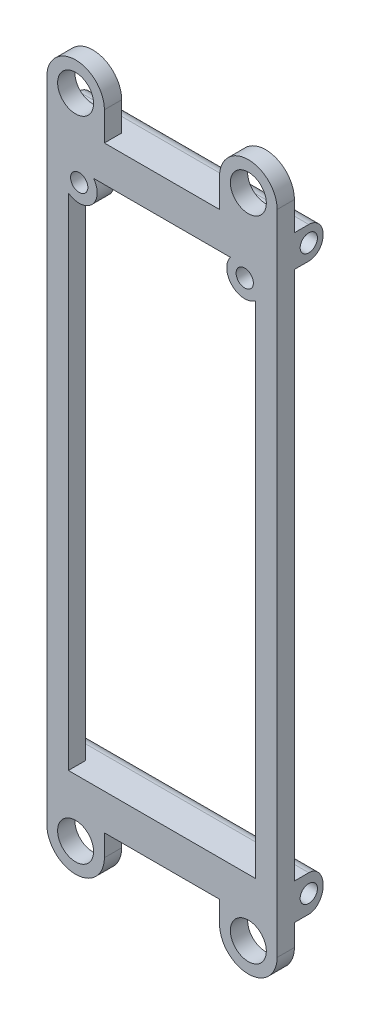
SolidWorks part; units mm, degrees
ref_plane "Front Plane" through (0, 0, 0) normal (0, 0, 1) x (1, 0, 0)
ref_plane "Top Plane" through (0, 0, 0) normal (0, 1, 0) x (1, 0, 0)
ref_plane "Right Plane" through (0, 0, 0) normal (1, 0, 0) x (0, 0, -1)
sketch "Sketch1" plane through (0, 0, 0) normal (0, 0, 1) x (1, 0, 0)
  line L0 (16, -82) -> (16, 1) construction
  line L1 (8, 1) -> (24, 1)
  line L2 (0, 0) -> (0, -80)
  line L3 (8, -82) -> (24, -82)
  line L4 (32, 0) -> (32, -80)
  line L5 (4, 5) -> (4, 0) construction
  line L6 (0, 0) -> (0, 18.809) construction
  line L7 (4, 5) -> (0, 5)
  line L8 (0, 5) -> (0, 0)
  line L9 (8, 5) -> (8, 1)
  line L10 (0, 5) -> (0, 0)
  line L11 (28, 5) -> (28, 2.5) construction
  line L12 (32, 5) -> (32, 0)
  line L13 (24, 5) -> (24, 1)
  line L14 (32, 5) -> (32, 0)
  line L15 (28, 5) -> (32, 5)
  line L16 (29, -4) -> (3, -4)
  line L17 (3, -4) -> (3, -77)
  line L18 (3, -77) -> (29, -77)
  line L19 (29, -4) -> (29, -77)
  line L20 (0, -40) -> (32, -40) construction
  line L21 (28, -85) -> (28, -82.5) construction
  line L22 (4, -85) -> (4, -80) construction
  line L23 (28, -85) -> (32, -85)
  line L24 (32, -85) -> (32, -80)
  line L25 (8, -85) -> (8, -82)
  line L26 (32, -85) -> (32, -80)
  line L27 (0, -85) -> (0, -80)
  line L28 (24, -85) -> (24, -82)
  line L29 (0, -85) -> (0, -80)
  line L30 (4, -85) -> (0, -85)
  circle A0 centre (4, 5) radius 2.5
  arc A1 (8, 5) -> (0, 5) centre (4, 5) ccw
  arc A2 (24, 5) -> (32, 5) centre (28, 5) cw
  circle A3 centre (28, 5) radius 2.5
  circle A4 centre (28, -85) radius 2.5
  arc A5 (24, -85) -> (32, -85) centre (28, -85) ccw
  arc A6 (8, -85) -> (0, -85) centre (4, -85) cw
  circle A7 centre (4, -85) radius 2.5
  point P25 (16, -77)
  point P26 (16, -4)
  dimension "D2" = 5
  dimension "D1" = 32
  dimension "D3" = 5
  dimension "D4" = 4
  dimension "D5" = 80
  dimension "D6" = 3
  dimension "D7" = 5
  dimension "D8" = 5
  dimension "D9" = 73
extrude "Boss-Extrude1" add sketch "Sketch1" along normal blind 2.4
sketch "Sketch3" plane through (0, 0, 0) normal (0, 0, -1) x (-1, 0, 0)
  line L0 (0, 5) -> (0, -85) construction
  line L1 (0, -3.4178) -> (-32, -3.4178)
  line L2 (0, -3.4178) -> (0, 1)
  line L3 (0, 1) -> (-24, 1)
  line L5 (-32, -85) -> (-32, 5) construction
  line L6 (-24, 1) -> (-32, 1)
  line L9 (-32, 1) -> (-32, -3.4178)
  line L11 (-29, -77) -> (-8, -77)
  line L13 (-32, -82) -> (-8, -82)
  line L15 (-8, -82) -> (0, -82)
  line L17 (-8, -77) -> (0, -77)
  line L18 (0, -82) -> (0, -77)
  line L21 (-29, -77) -> (-32, -77)
  line L22 (-32, -82) -> (-32, -77)
extrude "Boss-Extrude2" add sketch "Sketch3" along normal blind 4
sketch "Sketch4" plane through (32, 0, 0) normal (1, 0, 0) x (0, 0, -1)
  line L0 (0, 1) -> (0, -3.4178) construction
  line L1 (0, -1.2089) -> (4, -1.2089) construction
  line L2 (4, 1) -> (4, -3.4178) construction
  line L3 (2, 1) -> (3.1873, 3.1291)
  line L4 (3.1873, 3.1291) -> (6.1042, 0.8279)
  line L5 (6.1042, 0.8279) -> (6.1042, -5.1232)
  line L6 (6.1042, -5.1232) -> (2, -5.1232)
  line L7 (2, -5.1232) -> (2, -3.4178)
  circle A0 centre (2, -1.2089) radius 1.2
  ellipse E0 centre (2, -1.2089) end of major axis (2, 1) minor radius 2 (2, -3.4178) -> (2, 1) ccw
  dimension "D1" = 2.4
extrude "Cut-Extrude1" cut sketch "Sketch4" against normal up to surface (32 mm away) up to face at (0, -40.2363, -0.9333)
sketch "Sketch5" plane through (32, 0, 0) normal (1, 0, 0) x (0, 0, -1)
  line L0 (0, -77) -> (0, -82) construction
  line L1 (0, -79.5) -> (4, -79.5) construction
  line L2 (4, -77) -> (4, -82) construction
  line L4 (2, -77) -> (2, -72.7996)
  line L5 (2, -72.7996) -> (8.5794, -72.7996)
  line L6 (8.5794, -72.7996) -> (8.5794, -85.0398)
  line L7 (8.5794, -85.0398) -> (2, -85.0398)
  line L8 (2, -85.0398) -> (2, -82)
  circle A0 centre (2, -79.5) radius 1.2
  ellipse E0 centre (2, -79.5) end of major axis (2, -77) minor radius 2 (2, -82) -> (2, -77) ccw
  dimension "D1" = 2.4
extrude "Cut-Extrude2" cut sketch "Sketch5" against normal up to surface (32 mm away) contours A0 | L4 L5 L6 L7 L8 E0 up to face at (0, -1.2089, -3.2)
sketch "Sketch6" plane through (0, 0, 2.4) normal (0, 0, 1) x (1, 0, 0)
  line L0 (3, -4) -> (3, -77) construction
  line L1 (29, -4) -> (3, -4) construction
  line L2 (16, -4) -> (16, -77) construction
  line L3 (3, -77) -> (29, -77) construction
  circle A1 centre (4.5, -5.5) radius 2.5
  circle A2 centre (27.5, -5.5) radius 2.5
  dimension "D1" = 5
  dimension "D2" = 1.5
  dimension "D3" = 1.5
extrude "Boss-Extrude3" add sketch "Sketch6" against normal up to surface (2.4 mm away) up to face at (16, -40.3544, 0)
sketch "Sketch7" plane through (0, 0, 2.4) normal (0, 0, 1) x (1, 0, 0)
  line L0 (16, -4) -> (16, -77) construction
  line L1 (25.5, -4) -> (6.5, -4) construction
  line L2 (3, -77) -> (29, -77) construction
  circle A0 centre (4.5, -5.5) radius 1.2
  circle A1 centre (27.5, -5.5) radius 1.2
  dimension "D1" = 2.4
extrude "Cut-Extrude3" cut sketch "Sketch7" against normal up to surface (2.4 mm away) up to face at (30.5, -85, 0)
